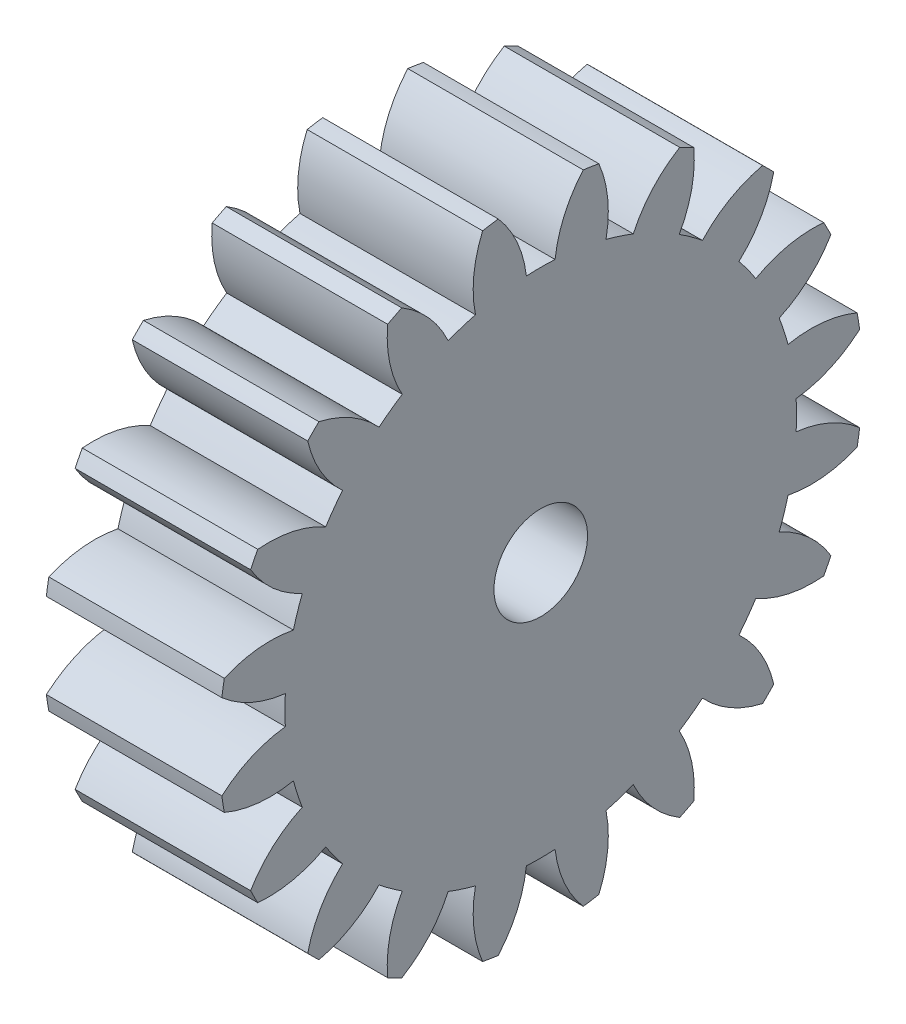
SolidWorks part; units mm, degrees
material "Простая углеродистая сталь"
ref_plane "Plane1" through (0, 0, 0) normal (0, 0, 1) x (1, 0, 0)
ref_plane "Plane2" through (0, 0, 0) normal (0, 1, 0) x (1, 0, 0)
ref_plane "Plane3" through (0, 0, 0) normal (1, 0, 0) x (0, 0, -1)
sketch "HoldingSke" plane through (0, 0, 0) normal (0, 1, 0) x (1, 0, 0)
  line L0 (0, 0) -> (3.7588, -1.3681)
  line L1 (-15, 0) -> (100, 0) construction
  line L2 (0, 0) -> (-2.1039, 2.3779)
  line L3 (0, 0) -> (-11.863, 4.5341)
  line L4 (0, 0) -> (8.1152, 2.9537)
  line L5 (0, 0) -> (-46.8476, -17.4728)
  line L6 (0, 0) -> (-1.2434, -0.839)
  line L7 (-2.1039, 2.3779) -> (8.6586, 51.2059)
  line L8 (-76.2, 54.61) -> (-76.1, 54.61)
  line L9 (-71.009, 38.7566) -> (-53.1078, 45.2721)
  line L10 (-76.2, 71.12) -> (104.1128, 71.12)
  line L11 (0, 0) -> (-1.5, 0)
  line L12 (-76.2, 101.6) -> (-76.192, 101.6)
  line L13 (24.9733, 27.94) -> (52.9518, 28.4284)
  line L14 (24.9733, 27.94) -> (24.9743, 27.94)
  line L15 (24.9733, 27.94) -> (100.4006, 29.5858)
  line L16 (-63.627, -0.25) -> (-12.827, -0.25)
  circle A0 centre (0, 0) radius 0.4
  circle A1 centre (0, 0) radius 2.1865
  circle A2 centre (0, 0) radius 37.5
  circle A3 centre (0, 0) radius 0.4
  dimension "MHD" = 4.373
  dimension "Hub_dia" = 75
  dimension "Bore" = 0.8
  dimension "MBD" = 0.8
  dimension "Num_teeth" = 20
  dimension "Pitch" = 4
  dimension "Overall_len" = 50
  dimension "Show_teeth" = 20
  dimension "Thickness" = 1.5
  dimension "OAL" = 50.0001
  dimension "T_dim" = 0.1
  dimension "Ap" = 20
  dimension "H" = 19.05
  dimension "Pitch_radius" = 180.3128
  dimension "Width" = 1.5
  dimension "Backlash" = 0.008
  dimension "Addendum_fac" = 1
  dimension "Dedendum_fac" = 1.25
  dimension "Clearance_fac" = 0.25
  dimension "Dedendum_add" = 0.001
  dimension "Module" = 0.25
sketch "BasProSke" plane through (0, 0, 0) normal (0, 1, 0) x (1, 0, 0)
  line L0 (-10, 0) -> (60, 0) construction
  line L1 (0, 0) -> (0, 2.75)
  line L2 (0, 0) -> (1.5, 0)
  line L3 (1.5, 0) -> (1.5, 2.75)
  line L4 (1.5, 2.75) -> (0, 2.75)
  dimension "Thickness" = 1.5
  dimension "Diameter" = 5.5
revolve "Base-Revolve" add sketch "BasProSke" angle 360 about L0
sketch "TooCutSke" plane through (0, 0, 0) normal (1, 0, 0) x (0, 0, -1)
  line L1 (0, 0) -> (0, 107) construction
  line L2 (0, 0) -> (-0.2101, 2.4912) construction
  line L3 (0, 0) -> (-0.7801, 4.9253) construction
  line L4 (-0.2101, 2.4912) -> (-0.39, 2.4627) construction
  arc A0 (0.1226, 2.1831) -> (-0.1226, 2.1831) centre (0, 0) ccw
  arc A1 (0.384, 2.7487) -> (-0.384, 2.7487) centre (0, 0) ccw
  circle A2 centre (0, 0) radius 2.5 construction
  circle A3 centre (0, 0) radius 2.3492 construction
  arc A4 (-0.1226, 2.1831) -> (-0.384, 2.7487) centre (-1.1159, 2.0673) ccw
  arc A5 (0.384, 2.7487) -> (0.1226, 2.1831) centre (1.1159, 2.0673) ccw
  dimension "Root_dia" = 4.373
  dimension "Overcut_dia" = 5.5508
  dimension "Pitch_dia" = 5
  dimension "Base_dia" = 4.6985
  dimension "Flank_rad" = 1
  dimension "Half_ang" = 9
  dimension "Half_CT" = 0.1821
extrude "ToothCut" cut sketch "TooCutSke" along normal through all
fillet "Breaks" [suppressed] radius 0.005
fillet "RootFillets" [suppressed] radius 0.0635
pattern_circular "TeethCuts" count 20 every 18 about axis through (-10, 0, 0) along (1, 0, 0) of "ToothCut", "RootFillets", "Breaks"
sketch "HubNeaOneSke" plane through (0, 0, 0) normal (-1, 0, 0) x (0, 0, 1)
  circle A0 centre (0, 0) radius 2.1865
  dimension "Diameter" = 4.373
extrude "HubNearOne" [suppressed] add sketch "HubNeaOneSke" along normal blind 48.5001
sketch "HubNeaBotSke" plane through (0, 0, 0) normal (-1, 0, 0) x (0, 0, 1)
  circle A0 centre (0, 0) radius 2.1865
  dimension "Diameter" = 4.373
extrude "HubNearBoth" [suppressed] add sketch "HubNeaBotSke" along normal blind 24.25
ref_plane "FarPln" through (1.5, 0, 0) normal (1, 0, 0) x (0, 0, -1)
sketch "HubFarSke" plane through (1.5, 0, 0) normal (1, 0, 0) x (0, 0, -1)
  circle A0 centre (0, 0) radius 2.1865
  dimension "Diameter" = 4.373
extrude "HubFar" [suppressed] add sketch "HubFarSke" along normal blind 24.25
sketch "BorSke" plane through (0, 0, 0) normal (1, 0, 0) x (0, 0, -1)
  circle A0 centre (0, 0) radius 0.4
  dimension "Diameter" = 0.8
extrude "Bore" cut sketch "BorSke" along normal mid plane 100.0001
sketch "KeySke" plane through (0, 0, 0) normal (1, 0, 0) x (0, 0, -1)
  line L0 (-0.05, 0) -> (-0.05, 0.5)
  line L1 (-0.05, 0.5) -> (0.05, 0.5)
  line L2 (0.05, 0.5) -> (0.05, 0)
  line L3 (0, 0) -> (0, 34) construction
  line L4 (-0.05, 0) -> (0.05, 0)
  dimension "Offset" = 0.5
  dimension "Width" = 0.1
extrude "Keyway" [suppressed] cut sketch "KeySke" along normal mid plane 100.0001
pattern_circular "Keyway2" [suppressed] count 2 every 90 about axis through (-10, 0, 0) along (1, 0, 0)
equation "' \"Module@HoldingSke\" = 6.35"
equation "' \"Num_teeth@HoldingSke\" = 12"
equation "' \"Ap@HoldingSke\" =  20"
equation "' \"Ap@HoldingSke\" = 20"
equation "' \"Width@HoldingSke\" = 0.5 * 25.4"
equation "' \"Hub_dia@HoldingSke\"= 1 * 25.4"
equation "' \"Hub_dia@HoldingSke\" = 1 * 25.4"
equation "' \"Overall_len@HoldingSke\" = 1.0 * 25.4"
equation "' \"Bore@HoldingSke\" = 0.75 * 25.4"
equation "' \"T_dim@HoldingSke\" = 0.1 * 25.4"
equation "' \"Width@KeySke\" = 0.25 * 25.4"
equation "' \"Show_teeth@HoldingSke\" = 13"
equation "' \"Backlash@HoldingSke\" = 0.009 * 25.4"
equation "' \"Addendum_fac@HoldingSke\" = 1.0"
equation "' \"Dedendum_fac@HoldingSke\" = 1.25"
equation "' \"Dedendum_add@HoldingSke\" = 0.00005 * 25.4"
equation "' \"Clearance_fac@HoldingSke\" = 0.25"
equation "\"Pitch@HoldingSke\" = 1 / \"Module@HoldingSke\""
equation "\"Overcut_dia@TooCutSke\" = (\"Num_teeth@HoldingSke\" + 2 * \"Addendum_fac@HoldingSke\") / \"Pitch@HoldingSke\" + 0.002 * 25.4"
equation "\"Pitch_dia@TooCutSke\" = \"Num_teeth@HoldingSke\" / \"Pitch@HoldingSke\""
equation "\"Base_dia@TooCutSke\" = \"Num_teeth@HoldingSke\" / \"Pitch@HoldingSke\" * cos((\"Ap@HoldingSke\"  * 3.14159265 / 180))"
equation "\"Root_dia@TooCutSke\" = (\"Num_teeth@HoldingSke\" + 2) / \"Pitch@HoldingSke\" - 2 * (\"Addendum_fac@HoldingSke\" + \"Dedendum_fac@HoldingSke\") / \"Pitch@HoldingSke\" - \"Dedendum_add@HoldingSke\" * 2"
equation "\"Half_ang@TooCutSke\" = 180 / \"Num_teeth@HoldingSke\""
equation "\"Half_CT@TooCutSke\" = \"Num_teeth@HoldingSke\" / \"Pitch@HoldingSke\" * sin((3.14159265 / 2 / \"Num_teeth@HoldingSke\")) / 2 - 7 * \"Backlash@HoldingSke\" / 4"
equation "\"Flank_rad@TooCutSke\" = \"Num_teeth@HoldingSke\" / \"Pitch@HoldingSke\" / 5"
equation "\"Radius@RootFillets\" = \"Clearance_fac@HoldingSke\" / \"Pitch@HoldingSke\" + \"Dedendum_add@HoldingSke\""
equation "\"Break_rad@Breaks\" = 0.02 / \"Pitch@HoldingSke\""
equation "\"Thickness@HoldingSke\" = \"Width@HoldingSke\""
equation "\"OAL@HoldingSke\" = \"Thickness@HoldingSke\""
equation "\"MHD@HoldingSke\" = (\"Num_teeth@HoldingSke\" + 2) / \"Pitch@HoldingSke\" - 2 * (\"Addendum_fac@HoldingSke\" + \"Dedendum_fac@HoldingSke\")  / \"Pitch@HoldingSke\" - \"Dedendum_add@HoldingSke\" * 2"
equation "\"MBD@HoldingSke\" = (\"Num_teeth@HoldingSke\" + 2) / \"Pitch@HoldingSke\" - 2 * (\"Addendum_fac@HoldingSke\" + \"Dedendum_fac@HoldingSke\")  / \"Pitch@HoldingSke\" - \"Dedendum_add@HoldingSke\" * 2 - 0.002 * 25.4"
equation "\"MHD@HoldingSke\" = ((sgn( \"MHD@HoldingSke\" - \"Hub_dia@HoldingSke\" )-1)*( \"MHD@HoldingSke\" - \"Hub_dia@HoldingSke\" ))/-2+ \"Hub_dia@HoldingSke\""
equation "\"MBD@HoldingSke\" = ((sgn( \"MBD@HoldingSke\" - \"Bore@HoldingSke\" )-1)*( \"MBD@HoldingSke\" - \"Bore@HoldingSke\" ))/-2+ \"Bore@HoldingSke\""
equation "\"OAL@HoldingSke\" = ((sgn( \"OAL@HoldingSke\" - \"Overall_len@HoldingSke\" )+1)*( \"OAL@HoldingSke\" - \"Overall_len@HoldingSke\" ))/2 + \"Overall_len@HoldingSke\" + 0.000002 * 25.4"
equation "\"Num_teeth@TeethCuts\" = int( \"Show_teeth@HoldingSke\" ) + 1"
equation "\"Num_teeth@TeethCuts\" = ((sgn( \"Num_teeth@TeethCuts\" - \"Num_teeth@HoldingSke\" )-1)*( \"Num_teeth@TeethCuts\" - \"Num_teeth@HoldingSke\" ))/-2+ \"Num_teeth@HoldingSke\""
equation "\"Num_teeth@TeethCuts\" = ((sgn( \"Num_teeth@TeethCuts\" - 2.0)+1)*( \"Num_teeth@TeethCuts\" - 2.0))/2 +2.0"
equation "\"Angle@TeethCuts\" = 360.0 / \"Num_teeth@HoldingSke\""
equation "\"Diameter@BasProSke\" = (\"Num_teeth@HoldingSke\" + 2 * \"Addendum_fac@HoldingSke\") / \"Pitch@HoldingSke\""
equation "\"Thickness@BasProSke\"  = \"Thickness@HoldingSke\""
equation "' \"Fillet_rad@BasProSke\" =  \"Thickness@HoldingSke\" * 0.05"
equation "' \"Fillet_rad@BasProSke\" = \"Thickness@HoldingSke\" * 0.05"
equation "\"MHD@HoldingSke\" = ((sgn( \"MHD@HoldingSke\" - \"Root_dia@TooCutSke\" )-1)*( \"MHD@HoldingSke\" - \"Root_dia@TooCutSke\" ))/-2+ \"Root_dia@TooCutSke\""
equation "\"Diameter@HubNeaOneSke\" = \"MHD@HoldingSke\""
equation "\"Length@HubNearOne\" = \"OAL@HoldingSke\" - \"Thickness@BasProSke\""
equation "\"Diameter@HubNeaBotSke\" = \"MHD@HoldingSke\""
equation "\"Length@HubNearBoth\" = ( \"OAL@HoldingSke\" - \"Thickness@BasProSke\" ) / 2.0"
equation "\"Thickness@FarPln\" = \"Thickness@BasProSke\""
equation "\"Diameter@HubFarSke\" = \"MHD@HoldingSke\""
equation "\"Length@HubFar\" = ( \"OAL@HoldingSke\" - \"Thickness@BasProSke\" ) / 2.0"
equation "\"Diameter@BorSke\" = \"MBD@HoldingSke\""
equation "\"D1@Bore\" = \"OAL@HoldingSke\" * 2.0"
equation "\"D1@Keyway\" = \"OAL@HoldingSke\" * 2.0"
equation "\"Offset@KeySke\" = \"T_dim@HoldingSke\" + \"MBD@HoldingSke\" / 2.0"
